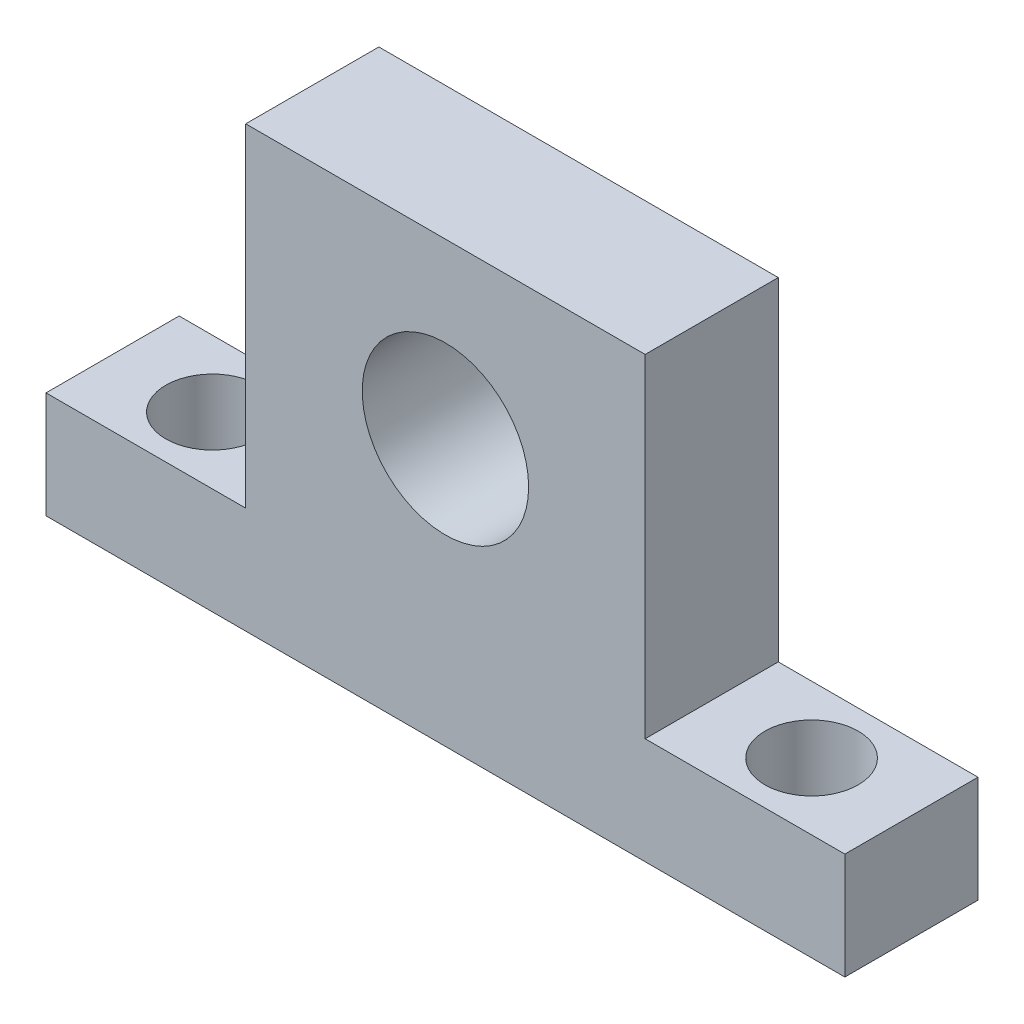
SolidWorks part; units mm, degrees
ref_plane "前基準面" through (0, 0, 0) normal (0, 0, 1) x (1, 0, 0)
ref_plane "上基準面" through (0, 0, 0) normal (0, 1, 0) x (1, 0, 0)
ref_plane "右基準面" through (0, 0, 0) normal (1, 0, 0) x (0, 0, -1)
sketch "草圖1" plane through (0, 0, 0) normal (0, 0, 1) x (1, 0, 0)
  line L0 (30, 0) -> (45, 0)
  line L2 (0, 0) -> (0, 25)
  line L3 (0, 25) -> (30, 25)
  line L4 (30, 0) -> (30, 25)
  line L5 (-15, 0) -> (0, 0)
  line L6 (-15, 0) -> (-15, -8)
  line L7 (-15, -8) -> (45, -8)
  line L8 (45, 0) -> (45, -8)
  circle A0 centre (15, 12) radius 6.25
  point P11 (15, 25)
  point P12 (15, -8)
  dimension "D1" = 12.5
  dimension "D2" = 20
  dimension "D3" = 8
  dimension "D4" = 25
  dimension "D5" = 30
  dimension "D6" = 15
extrude "填料-伸長1" add sketch "草圖1" along normal blind 10 contours A0 | L2 L3 L4 L0 L8 L7 L6 L5
sketch "草圖2" plane through (0, 0, 0) normal (0, 1, 0) x (1, 0, 0)
  line L0 (30, -10) -> (45, -10) construction
  line L1 (45, -10) -> (45, 0) construction
  circle A0 centre (37.5, -5) radius 3.5
  point P5 (37.5, -10)
  point P9 (45, -5)
  dimension "D1" = 7
extrude "除料-伸長2" cut sketch "草圖2" against normal through all contours A0
sketch "草圖3" plane through (0, 0, 0) normal (0, 1, 0) x (1, 0, 0)
  line L0 (-15, -10) -> (-15, 0) construction
  line L1 (-15, 0) -> (0, 0) construction
  circle A0 centre (-7.5, -5) radius 3.5
  point P5 (-15, -5)
  point P8 (-7.5, 0)
  dimension "D1" = 7
extrude "除料-伸長3" cut sketch "草圖3" against normal through all
